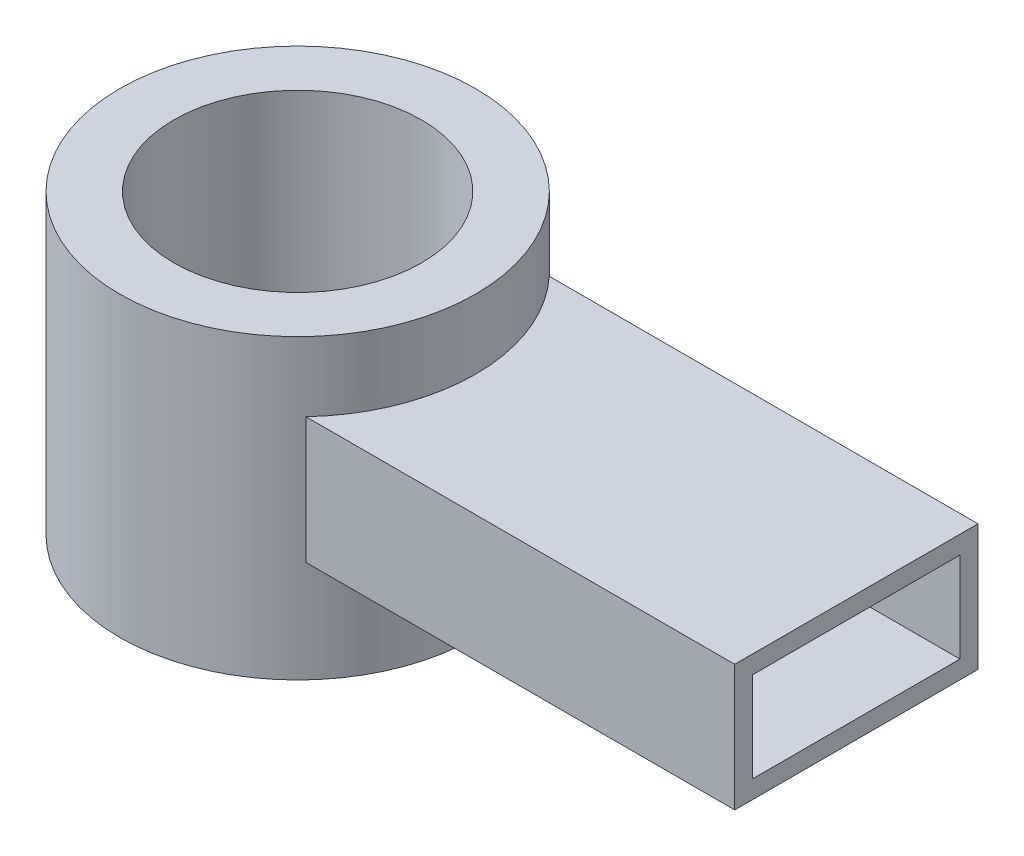
SolidWorks part; units mm, degrees
ref_plane "前基準面" through (0, 0, 0) normal (0, 0, 1) x (1, 0, 0)
ref_plane "上基準面" through (0, 0, 0) normal (0, 1, 0) x (1, 0, 0)
ref_plane "右基準面" through (0, 0, 0) normal (1, 0, 0) x (0, 0, -1)
sketch "管徑" plane through (0, 0, 0) normal (0, 1, 0) x (1, 0, 0)
  circle A0 centre (0, 0) radius 13.75
  dimension "D1" = 27.5
extrude "6分管 內直徑27.5厚度3長度10" add sketch "管徑" along normal blind 80 thin
ref_plane "平面1" through (10, 0, 0) normal (1, 0, 0) x (0, 0, -1)
sketch "草圖7" plane through (10, 0, 0) normal (1, 0, 0) x (0, 0, -1)
  line L0 (0, -1000) -> (0, 49000) construction
  line L2 (-13.5, 72.2993) -> (13.5, 72.2993)
  line L3 (-13.5, 72.2993) -> (-13.5, 58.2993)
  line L4 (-13.5, 58.2993) -> (13.5, 58.2993)
  line L5 (13.5, 72.2993) -> (13.5, 58.2993)
  line L6 (-13.5, 72.2993) -> (13.5, 58.2993) construction
  line L7 (-13.5, 58.2993) -> (13.5, 72.2993) construction
  point P1 (0, 65.2993)
  dimension "D1" = 27
  dimension "D2" = 14
extrude "填料-伸長2" add sketch "草圖7" along normal blind 52
sketch "草圖8" plane through (62, 0, 0) normal (1, 0, 0) x (0, 0, -1)
  line L0 (-13.5, 72.2993) -> (-13.5, 58.2993) construction
  line L1 (-11.5, 70.2993) -> (11.5, 70.2993)
  line L2 (-11.5, 70.2993) -> (-11.5, 60.2993)
  line L3 (-11.5, 60.2993) -> (11.5, 60.2993)
  line L4 (11.5, 70.2993) -> (11.5, 60.2993)
  line L5 (-11.5, 70.2993) -> (11.5, 60.2993) construction
  line L6 (-11.5, 60.2993) -> (11.5, 70.2993) construction
  line L7 (13.5, 58.2993) -> (13.5, 72.2993) construction
  line L8 (-13.5, 58.2993) -> (13.5, 58.2993) construction
  line L9 (13.5, 72.2993) -> (-13.5, 72.2993) construction
  point P0 (0, 65.2993)
  dimension "D1" = 2
  dimension "D2" = 2
  dimension "D3" = 2
  dimension "D4" = 2
extrude "除料-伸長1" cut sketch "草圖8" against normal blind 50
sketch "草圖9" plane through (0, 0, 0) normal (0, -1, 0) x (1, 0, 0)
  circle A0 centre (0, 0) radius 13.75
extrude "除料-伸長-薄件1" cut sketch "草圖9" against normal blind 47 thin
